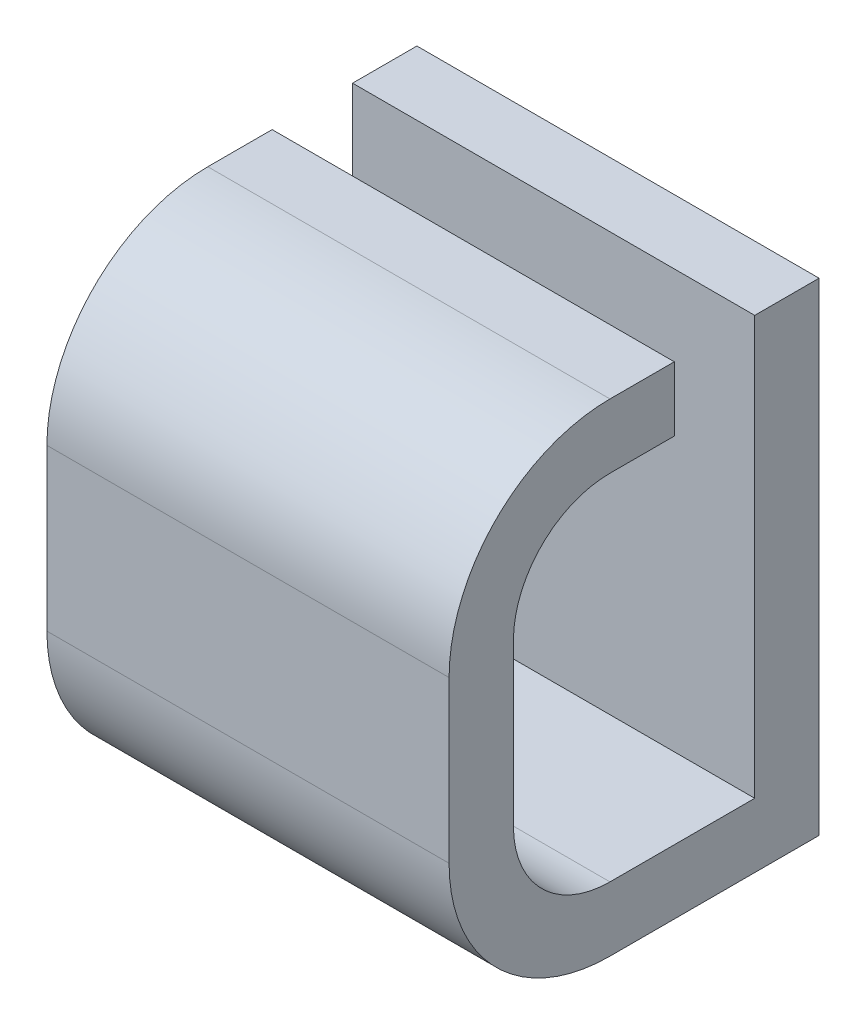
SolidWorks part; units mm, degrees
ref_plane "Спереди" through (0, 0, 0) normal (0, 0, 1) x (1, 0, 0)
ref_plane "Сверху" through (0, 0, 0) normal (0, 1, 0) x (1, 0, 0)
ref_plane "Справа" through (0, 0, 0) normal (1, 0, 0) x (0, 0, -1)
sketch "Эскиз2" plane through (0, 0, 0) normal (1, 0, 0) x (0, 0, -1)
  line L0 (-3.0187, 8.5091) -> (-3.0187, 2.5091)
  line L2 (-3.0187, 2.5091) -> (-5.6187, 2.5091)
  line L3 (-7.6187, 4.5091) -> (-7.6187, 6.5091)
  line L4 (-5.6187, 8.5091) -> (-4.8187, 8.5091)
  line L5 (-3.8187, 8.5091) -> (-3.8187, 3.3091)
  line L6 (-3.8187, 3.3091) -> (-5.6187, 3.3091)
  line L7 (-6.8187, 4.5091) -> (-6.8187, 6.5091)
  line L8 (-5.6187, 7.7091) -> (-4.8187, 7.7091)
  line L9 (-4.8187, 8.5091) -> (-4.8187, 7.7091)
  line L10 (-3.8187, 8.5091) -> (-3.0187, 8.5091)
  arc A0 (-5.6187, 2.5091) -> (-7.6187, 4.5091) centre (-5.6187, 4.5091) cw
  arc A1 (-7.6187, 6.5091) -> (-5.6187, 8.5091) centre (-5.6187, 6.5091) cw
  arc A2 (-5.6187, 3.3091) -> (-6.8187, 4.5091) centre (-5.6187, 4.5091) cw
  arc A3 (-6.8187, 6.5091) -> (-5.6187, 7.7091) centre (-5.6187, 6.5091) cw
  dimension "D1" = 2
  dimension "D3" = 3
  dimension "D4" = 6
  dimension "D5" = 1
  dimension "D2" = 0.8
extrude "Бобышка-Вытянуть1" add sketch "Эскиз2" along normal blind 5
